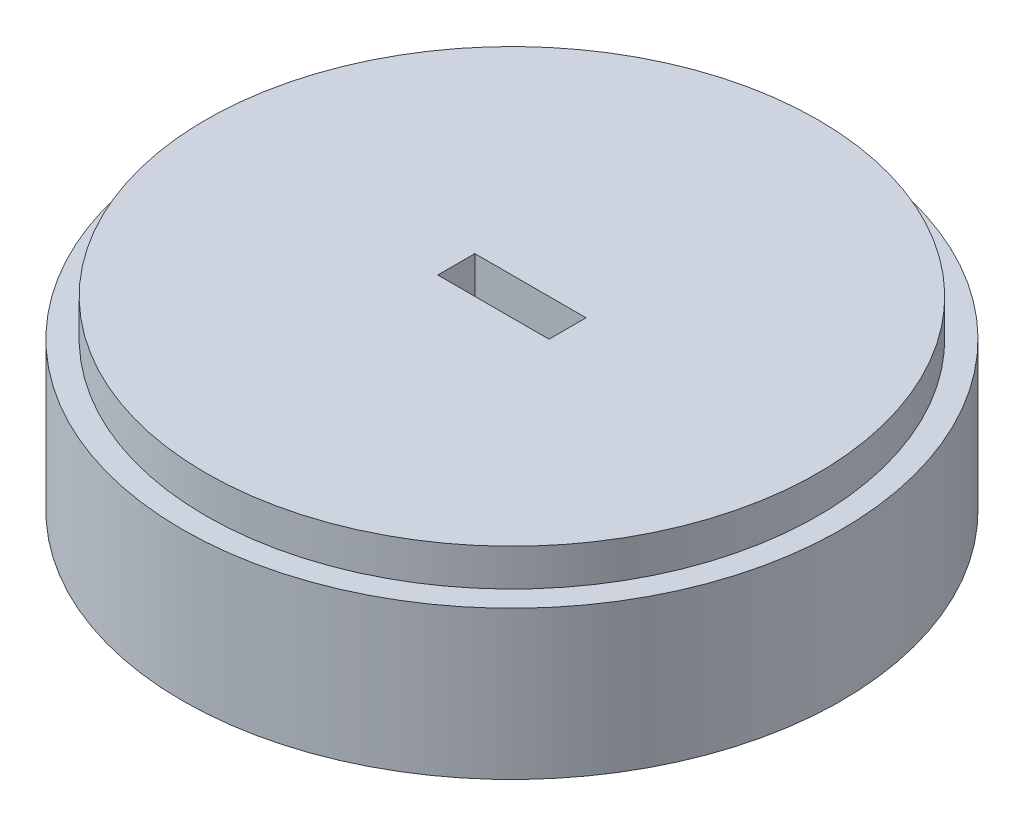
SolidWorks part; units mm, degrees
ref_plane "Front Plane" through (0, 0, 0) normal (0, 0, 1) x (1, 0, 0)
ref_plane "Top Plane" through (0, 0, 0) normal (0, 1, 0) x (1, 0, 0)
ref_plane "Right Plane" through (0, 0, 0) normal (1, 0, 0) x (0, 0, -1)
sketch "Sketch1" plane through (0, 0, 0) normal (0, 1, 0) x (1, 0, 0)
  circle A0 centre (0, 0) radius 88.9
  dimension "D1" = 177.8
extrude "Boss-Extrude1" add sketch "Sketch1" along normal blind 40
sketch "Sketch2" plane through (0, 40, 0) normal (0, 1, 0) x (1, 0, 0)
  circle A0 centre (0, 0) radius 82.55
  circle A1 centre (0, 0) radius 88.9 construction
  dimension "D1" = 6.35
extrude "Boss-Extrude2" add sketch "Sketch2" along normal blind 10
sketch "Sketch3" plane through (0, 0, 0) normal (0, 0, 1) x (1, 0, 0)
  line L0 (0, 0) -> (0, 32.5) construction
  line L1 (-15, 50) -> (15, 50)
  line L2 (-15, 50) -> (-15, 15)
  line L3 (-15, 15) -> (15, 15)
  line L4 (15, 50) -> (15, 15)
  line L5 (-15, 50) -> (15, 15) construction
  line L6 (-15, 15) -> (15, 50) construction
  line L7 (82.55, 50) -> (-82.55, 50) construction
  point P0 (0, 32.5)
  dimension "D1" = 30
  dimension "D2" = 35
extrude "Cut-Extrude1" cut sketch "Sketch3" against normal mid plane 10
